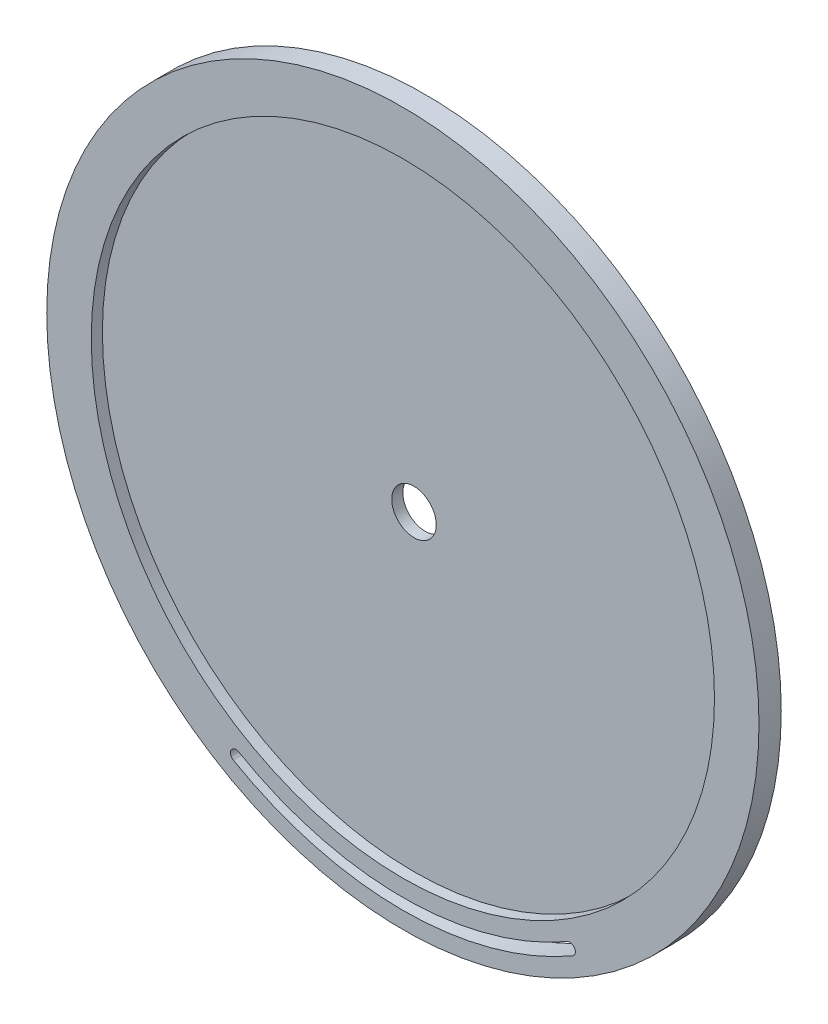
SolidWorks part; units mm, degrees
material "Brass"
ref_plane "Front Plane" through (0, 0, 0) normal (0, 0, 1) x (1, 0, 0)
ref_plane "Top Plane" through (0, 0, 0) normal (0, 1, 0) x (1, 0, 0)
ref_plane "Right Plane" through (0, 0, 0) normal (1, 0, 0) x (0, 0, -1)
sketch "Sketch1" plane through (0, 0, 0) normal (0, 0, 1) x (1, 0, 0)
  line L2 (-1000, 0) -> (49000, 0) construction
  line L3 (0, -1000) -> (0, 49000) construction
  circle A0 centre (0, 0) radius 101.6
  dimension "dial outer diameter" = 203.2
extrude "Radius" add sketch "Sketch1" along normal blind 6.35
sketch "Sketch4" plane through (0, 0, 6.35) normal (0, 0, 1) x (1, 0, 0)
  circle A0 centre (0, 0) radius 88.9
  dimension "dial inner diameter" = 177.8
extrude "Extrude4" cut sketch "Sketch4" against normal blind 3.175
sketch "Sketch7" plane through (0, 0, 6.35) normal (0, 0, 1) x (1, 0, 0)
  line L0 (0, -1000) -> (0, 49000) construction
  line L1 (0, 0) -> (25000, -43301.2702) construction
  line L2 (0, 0) -> (-25000, -43301.2702) construction
  arc A0 (47.625, -82.4889) -> (-47.625, -82.4889) centre (0, 0) cw
  arc A1 (46.8313, -81.1141) -> (-46.8313, -81.1141) centre (0, 0) cw
  arc A2 (48.4188, -83.8637) -> (-48.4188, -83.8637) centre (0, 0) cw
  arc A3 (46.8313, -81.1141) -> (48.4188, -83.8637) centre (47.625, -82.4889) cw
  arc A4 (-46.8313, -81.1141) -> (-48.4188, -83.8637) centre (-47.625, -82.4889) ccw
  dimension "D1" = 95.25
  dimension "D4" = 3.175
  dimension "D2" = 1.5875
  dimension "D3" = 1.5875
extrude "Extrude5" cut sketch "Sketch7" against normal through all
sketch "Sketch14" plane through (0, 0, 3.175) normal (0, 0, 1) x (1, 0, 0)
  circle A0 centre (0, 0) radius 6.35
  dimension "D1" = 12.7
extrude "Extrude6" cut sketch "Sketch14" against normal blind 6.35
equation "\"D1@Sketch3\" = \"dial outer diameter@Sketch1\"*3/8"
equation "\"dial inner diameter@Sketch4\"=\"dial outer diameter@Sketch1\"*3/4"
